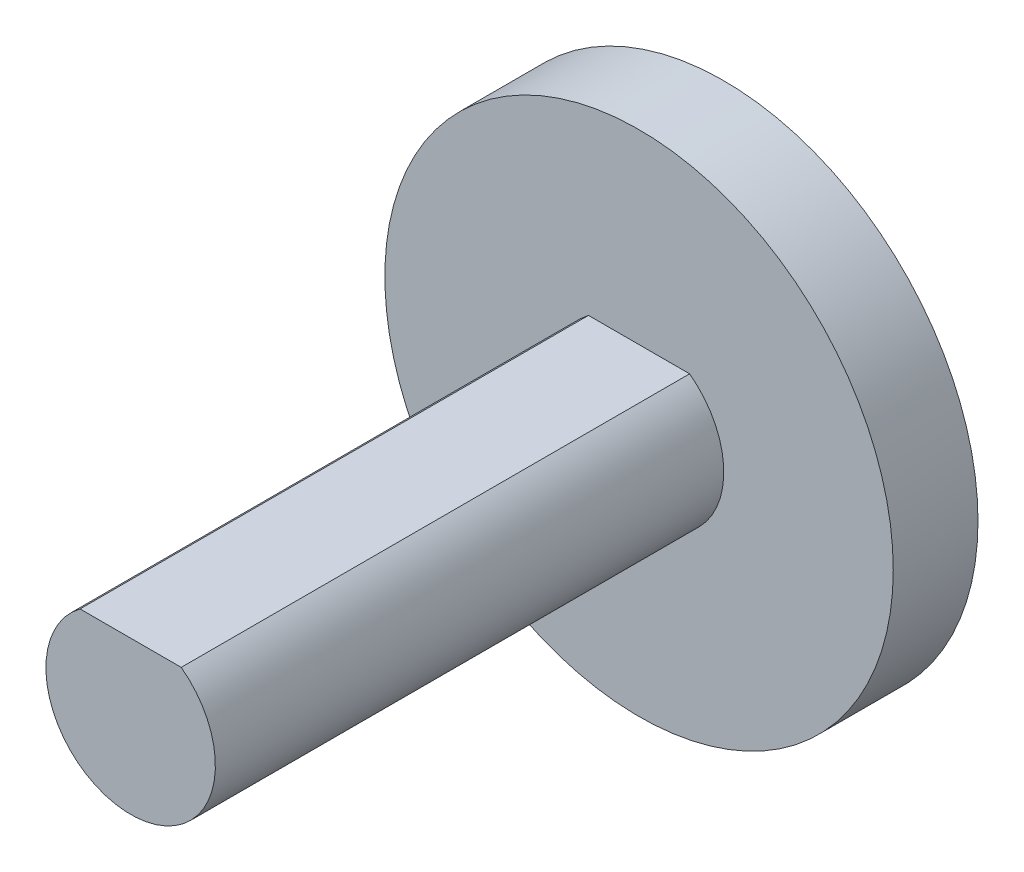
SolidWorks part; units mm, degrees
ref_plane "Front Plane" through (0, 0, 0) normal (1, 0, 0) x (0, 1, 0)
ref_plane "Top Plane" through (0, 0, 0) normal (0, 0, 1) x (0, 1, 0)
ref_plane "Right Plane" through (0, 0, 0) normal (0, 1, 0) x (-1, 0, 0)
sketch "Sketch1" plane through (0, 0, 0) normal (0, 0, 1) x (0, 1, 0)
  circle A0 centre (0, 0) radius 7.5
  dimension "D1" = 15
extrude "Boss-Extrude1" add sketch "Sketch1" along normal blind 2.5
sketch "Sketch2" plane through (0, 0, 2.5) normal (0, 0, 1) x (1, 0, 0)
  line L3 (-1.4923, 2.0058) -> (1.4923, 2.0058)
  arc A2 (-1.4923, 2.0058) -> (1.4923, 2.0058) centre (0, 0) ccw
  dimension "D2" = 5
extrude "Boss-Extrude3" add sketch "Sketch2" along normal blind 15 contours L3 A2
